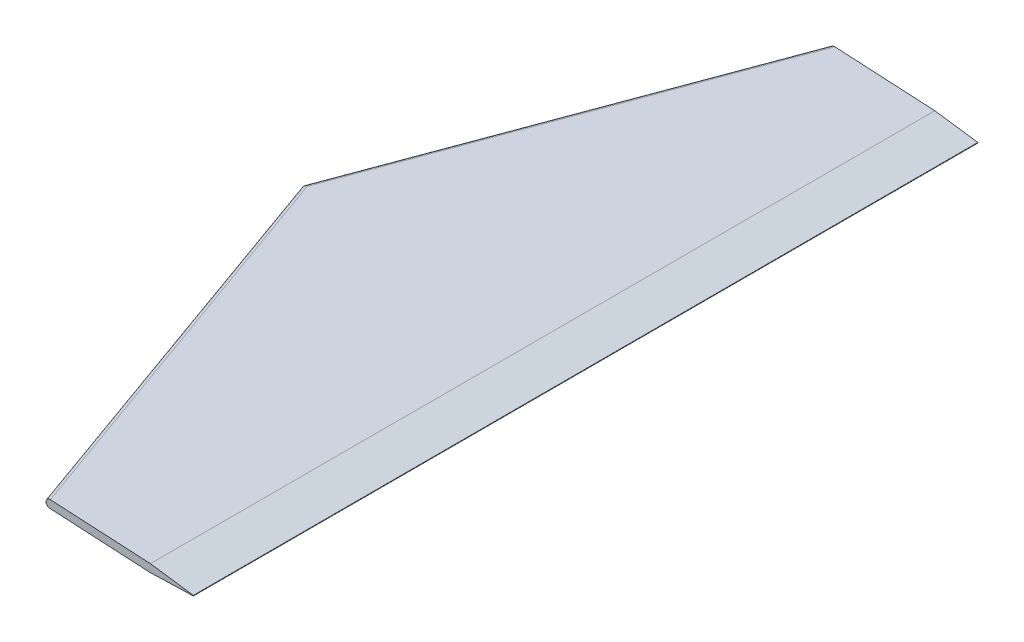
SolidWorks part; units mm, degrees
ref_plane "Front Plane" through (0, 0, 0) normal (0, 0, 1) x (1, 0, 0)
ref_plane "Top Plane" through (0, 0, 0) normal (0, 1, 0) x (1, 0, 0)
ref_plane "Right Plane" through (0, 0, 0) normal (1, 0, 0) x (0, 0, -1)
sketch "Sketch1" plane through (0, 0, 0) normal (0, 0, 1) x (1, 0, 0)
  line L0 (0, 0) -> (201.1072, -10.8564)
  line L1 (-20.6761, -33.7457) -> (37.2548, -33.7457)
  line L2 (0, 0) -> (0.2969, 5.5)
  line L3 (0.2969, 5.5) -> (201.4041, -5.3564)
  line L4 (201.4041, -5.3564) -> (201.1072, -10.8564)
  dimension "D1" = 3.09
  dimension "D2" = 201.4
  dimension "D3" = 5.5
extrude "Boss-Extrude1" add sketch "Sketch1" along normal mid plane 551.2 contours L3 L4 L0 L2
sketch "Sketch2" plane through (0.2969, 5.5, 0) normal (0.0539, 0.9985, 0) x (0.9985, -0.0539, 0)
  line L0 (0, 0) -> (95.4, 275.6)
  line L1 (0, 275.6) -> (201.4, 275.6) construction
  line L2 (95.4, 275.6) -> (0, 275.6)
  line L3 (0, 275.6) -> (0, 0)
  line L5 (201.4, -275.6) -> (201.4, 275.6) construction
  dimension "D1" = 106
  dimension "D2" = 19.093
extrude "Cut-Extrude1" cut sketch "Sketch2" against normal through all
sketch "Sketch3" plane through (0.2969, 5.5, 0) normal (0.0539, 0.9985, 0) x (0.9985, -0.0539, 0)
  line L0 (0, 0) -> (95.4, -275.6)
  line L1 (0, -275.6) -> (201.4, -275.6) construction
  line L2 (95.4, -275.6) -> (0, -275.6)
  line L3 (0, -275.6) -> (0, 0)
  dimension "D1" = 106
extrude "Cut-Extrude2" cut sketch "Sketch3" against normal through all
sketch "Sketch4" plane through (0, 0, 275.6) normal (0, 0, 1) x (1, 0, 0)
  line L0 (168.7516, -3.5937) -> (201.2556, -8.1064)
  line L1 (95.5582, 0.3575) -> (201.4041, -5.3564) construction
  line L2 (201.4041, -5.3564) -> (201.1072, -10.8564) construction
  line L3 (201.2556, -8.1064) -> (201.4041, -5.3564)
  line L4 (201.4041, -5.3564) -> (168.7516, -3.5937)
  dimension "D1" = 32.7
extrude "Cut-Extrude3" cut sketch "Sketch4" against normal through all
sketch "Sketch5" plane through (0, 0, 275.6) normal (0, 0, 1) x (1, 0, 0)
  line L0 (201.2556, -8.1064) -> (168.4547, -9.0937)
  line L1 (95.2613, -5.1425) -> (201.1072, -10.8564) construction
  line L2 (168.4547, -9.0937) -> (201.1072, -10.8564)
  line L3 (201.1072, -10.8564) -> (201.2556, -8.1064)
  dimension "D1" = 32.7
extrude "Cut-Extrude4" cut sketch "Sketch5" against normal through all
fillet "Fillet1" radius 2.75 4 edges at (47.6306, -2.5712, -137.8) (47.9276, 2.9288, -137.8) (47.6306, -2.5712, 137.8) (47.9276, 2.9288, 137.8)
sketch "Sketch6" plane through (0.2969, 5.5, 0) normal (0.0539, 0.9985, 0) x (0.9985, -0.0539, 0)
  line L0 (0, 0) -> (168.7, 0)
  line L1 (168.7, 275.6) -> (168.7, -275.6) construction
fillet "Fillet2" radius 0.2 1 edges at (201.2556, -8.1064, 0)
